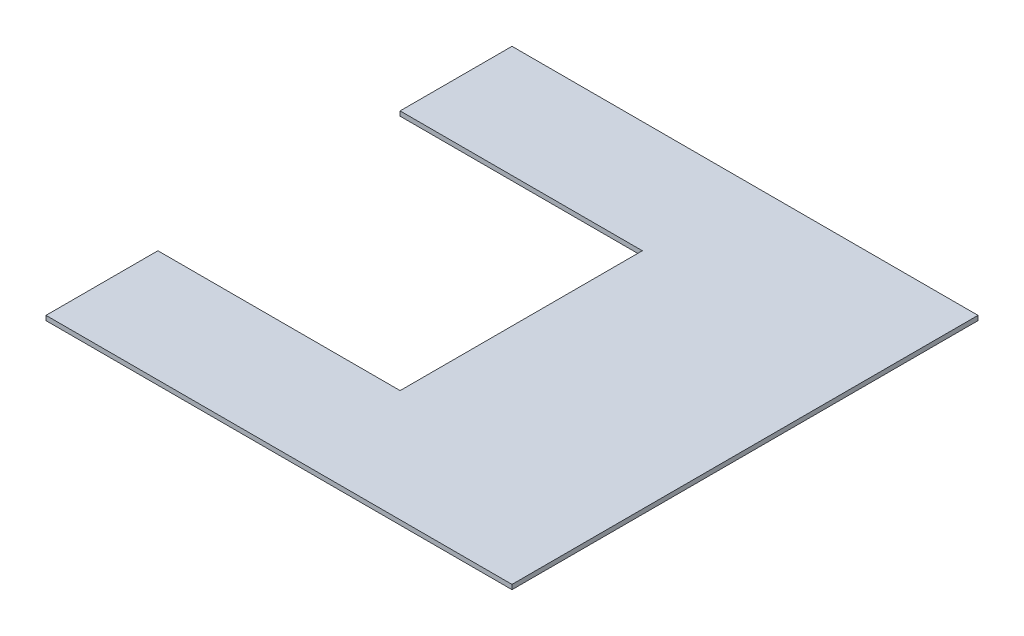
SolidWorks part; units mm, degrees
material "6061-T6 (SS)"
ref_plane "Alzado" through (0, 0, 0) normal (0, 0, 1) x (1, 0, 0)
ref_plane "Planta" through (0, 0, 0) normal (0, 1, 0) x (1, 0, 0)
ref_plane "Vista lateral" through (0, 0, 0) normal (1, 0, 0) x (0, 0, -1)
sketch "Sketch1" plane through (0, 0, 0) normal (0, 1, 0) x (1, 0, 0)
  line L1 (-101, 101) -> (101, 101)
  line L2 (-101, 101) -> (-101, -101)
  line L3 (-101, -101) -> (101, -101)
  line L4 (101, 101) -> (101, -101)
  line L5 (-101, 101) -> (101, -101) construction
  line L6 (-101, -101) -> (101, 101) construction
  point P0 (0, 0)
  dimension "D1" = 202
  dimension "D2" = 202
extrude "Boss-Extrude1" add sketch "Sketch1" along normal blind 2
sketch "Sketch2" plane through (0, 0, 0) normal (0, -1, 0) x (1, 0, 0)
  line L1 (-101, 52.5) -> (4, 52.5)
  line L2 (-101, 52.5) -> (-101, -52.5)
  line L3 (-101, -52.5) -> (4, -52.5)
  line L4 (4, 52.5) -> (4, -52.5)
  line L5 (-101, 52.5) -> (4, -52.5) construction
  line L6 (-101, -52.5) -> (4, 52.5) construction
  line L9 (-101, 0) -> (225.4376, 0) construction
  line L10 (-101, -101) -> (-101, 101) construction
  line L11 (101, 101) -> (101, -101) construction
  point P0 (-48.5, 0)
  dimension "D1" = 105
  dimension "D2" = 105
extrude "Cut-Extrude1" cut sketch "Sketch2" against normal up to next
